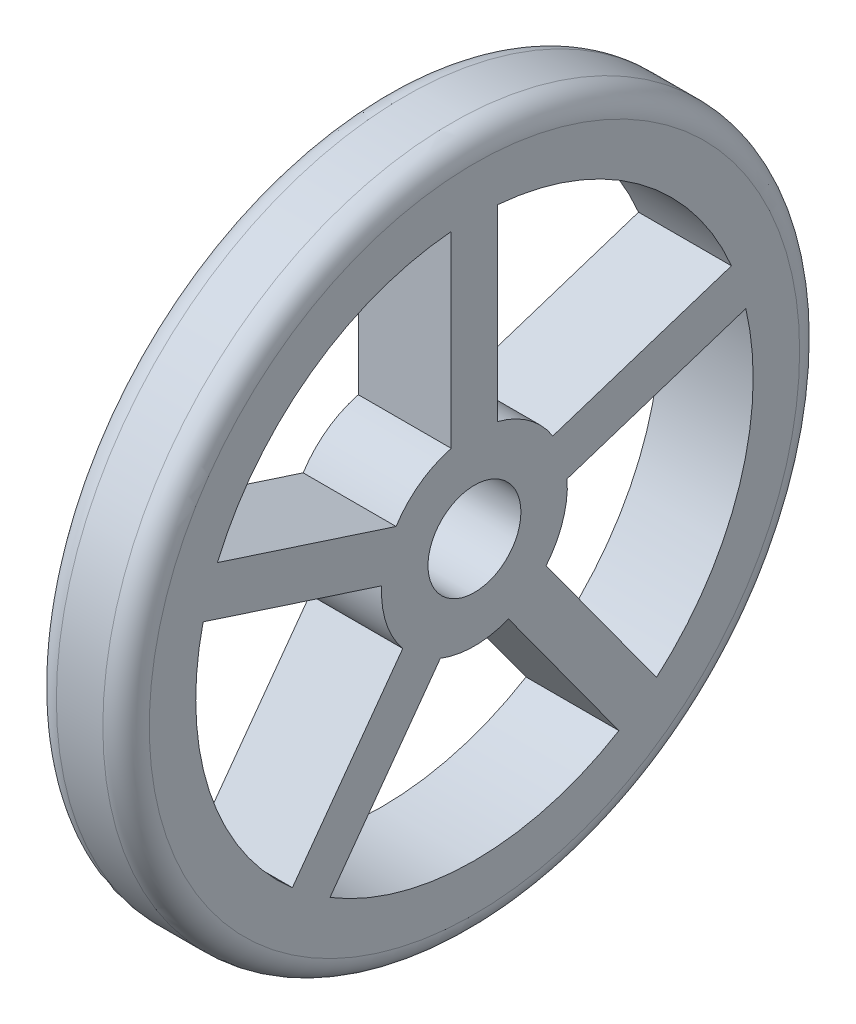
SolidWorks part; units mm, degrees
ref_plane "Front Plane" through (0, 0, 0) normal (0, 0, 1) x (1, 0, 0)
ref_plane "Top Plane" through (0, 0, 0) normal (0, 1, 0) x (1, 0, 0)
ref_plane "Right Plane" through (0, 0, 0) normal (1, 0, 0) x (0, 0, -1)
sketch "Sketch2" plane through (0, 0, 0) normal (1, 0, 0) x (0, 0, -1)
  line L0 (110.6396, 46.4636) -> (33.7441, 21.4787)
  line L2 (-10, 119.5826) -> (-10, 38.7298)
  line L4 (10, 119.5826) -> (10, 38.7298)
  line L5 (116.82, 27.4425) -> (39.9244, 2.4576)
  line L6 (78.3791, -90.8665) -> (30.855, -25.4552)
  line L7 (62.1987, -102.6222) -> (14.6747, -37.2109)
  line L8 (-62.1987, -102.6222) -> (-14.6747, -37.2109)
  line L9 (-78.3791, -90.8665) -> (-30.855, -25.4552)
  line L10 (-116.82, 27.4425) -> (-39.9244, 2.4576)
  line L11 (-110.6396, 46.4636) -> (-33.7441, 21.4787)
  circle A0 centre (0, 0) radius 20
  arc A1 (-10, 38.7298) -> (-33.7441, 21.4787) centre (0, 0) ccw
  arc A2 (-10, 119.5826) -> (-110.6396, 46.4636) centre (0, 0) ccw
  circle A3 centre (0, 0) radius 150
  arc A4 (-39.9244, 2.4576) -> (-30.855, -25.4552) centre (0, 0) ccw
  arc A5 (-116.82, 27.4425) -> (-78.3791, -90.8665) centre (0, 0) ccw
  arc A6 (-62.1987, -102.6222) -> (62.1987, -102.6222) centre (0, 0) ccw
  arc A7 (-14.6747, -37.2109) -> (14.6747, -37.2109) centre (0, 0) ccw
  arc A8 (30.855, -25.4552) -> (39.9244, 2.4576) centre (0, 0) ccw
  arc A9 (78.3791, -90.8665) -> (116.82, 27.4425) centre (0, 0) ccw
  arc A10 (110.6396, 46.4636) -> (10, 119.5826) centre (0, 0) ccw
  arc A11 (33.7441, 21.4787) -> (10, 38.7298) centre (0, 0) ccw
  point P29 (0, 0)
  dimension "D1" = 40
  dimension "D2" = 80
  dimension "D3" = 240
  dimension "D4" = 300
  dimension "D5" = 5
extrude "Boss-Extrude1" add sketch "Sketch2" along normal blind 40
fillet "Fillet1" radius 10 2 edges at (0, 0, -150) (40, 0, -150)
